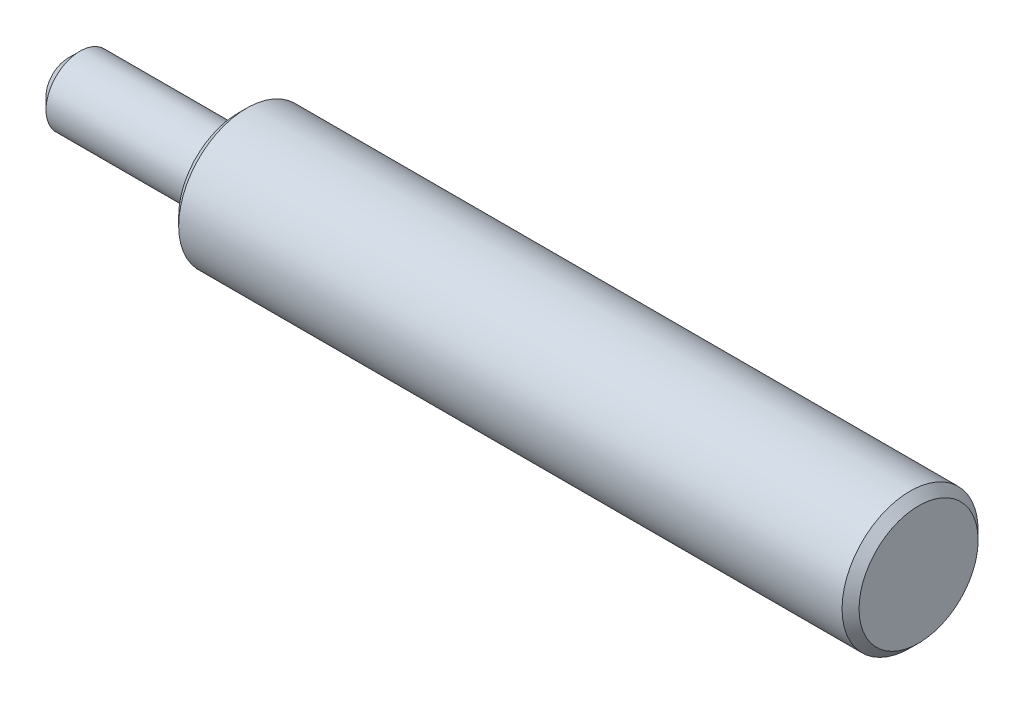
SolidWorks part; units mm, degrees
ref_plane "Front Plane" through (0, 0, 0) normal (0, 0, 1) x (1, 0, 0)
ref_plane "Top Plane" through (0, 0, 0) normal (0, 1, 0) x (1, 0, 0)
ref_plane "Right Plane" through (0, 0, 0) normal (1, 0, 0) x (0, 0, -1)
ref_plane "Plane1" through (0, 0, 0) normal (0, 0, 1) x (1, 0, 0)
sketch "Sketch1" plane through (0, 0, 0) normal (0, 0, 1) x (1, 0, 0)
  line L0 (-10, 0) -> (-10, 1.3)
  line L1 (-10, 1.3) -> (-9.3, 2)
  line L2 (-9.3, 2) -> (-0.3, 2)
  line L3 (0, 2.3) -> (0, 3.5)
  line L4 (0, 3.5) -> (0.5, 4)
  line L5 (0.5, 4) -> (39.5, 4)
  line L6 (39.5, 4) -> (40, 3.5)
  line L7 (40, 3.5) -> (40, 0)
  line L8 (40, 0) -> (-10, 0)
  line L9 (40, 0) -> (-10, 0) construction
  arc A0 (-0.3, 2) -> (0, 2.3) centre (-0.3, 2.3) ccw
revolve "Revolve1" add sketch "Sketch1" angle 360 about L9
